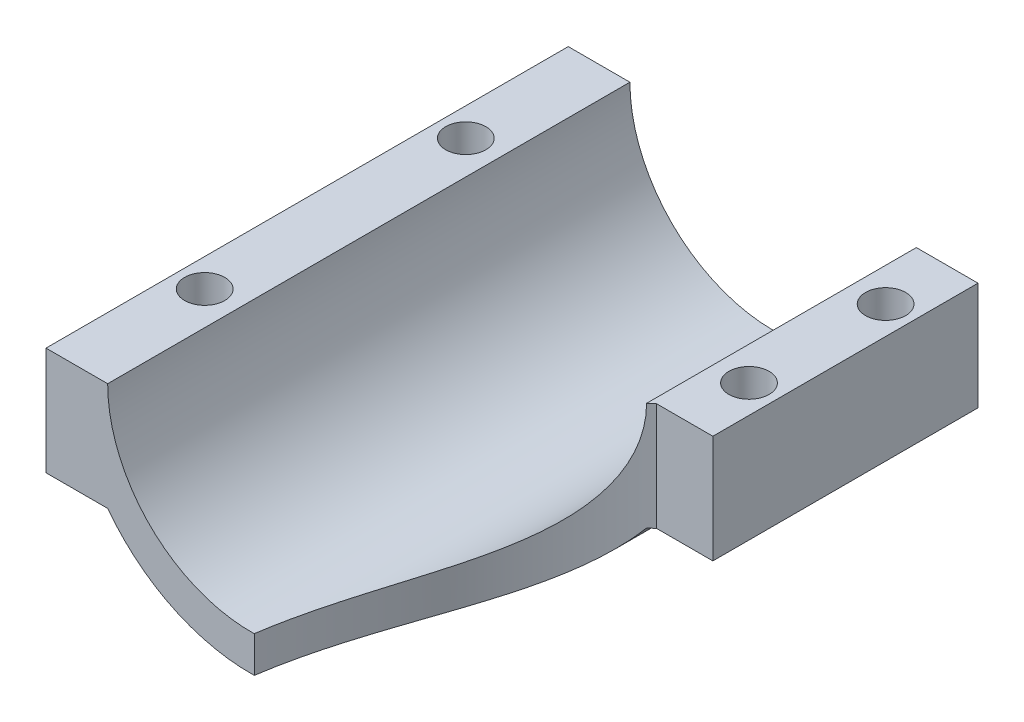
SolidWorks part; units mm, degrees
ref_plane "Front Plane" through (0, 0, 0) normal (0, 0, 1) x (1, 0, 0)
ref_plane "Top Plane" through (0, 0, 0) normal (0, 1, 0) x (1, 0, 0)
ref_plane "Right Plane" through (0, 0, 0) normal (1, 0, 0) x (0, 0, -1)
sketch "Sketch1" plane through (0, 0, 0) normal (0, 1, 0) x (1, 0, 0)
  line L4 (-18.5, -0.5) -> (-25.5, -0.5)
  line L5 (-25.5, -0.5) -> (-25.5, 32.5)
  line L6 (-22, -0.5) -> (-22, 32.5) construction
  line L7 (18.5, -32.5) -> (18.5, 32.5)
  line L8 (25.5, 32.5) -> (25.5, -32.5)
  line L9 (-18.5, -0.5) -> (-18.5, 32.5)
  line L10 (-25.5, 32.5) -> (25.5, 32.5)
  line L14 (25.5, -32.5) -> (-0.42, -32.5)
  line L22 (-18.5, 32.5) -> (18.5, -32.5) construction
  line L23 (-18.5, -0.5) -> (-18.5, -32.5) construction
  line L24 (-18.5, -32.5) -> (-0.42, -32.5) construction
  line L25 (-18.5, -32.5) -> (18.5, 32.5) construction
  arc A0 (-0.42, -32.5) -> (-18.5, -0.5) centre (-51.5792, -40.2973) ccw
  circle A1 centre (-22, 7.5) radius 2.5
  circle A2 centre (-22, 24.5) radius 2.5
  circle A3 centre (22, -16.25) radius 2.5
  circle A4 centre (22, 16.25) radius 2.5
  point P2 (0, 0)
  dimension "D3" = 5
  dimension "D4" = 5
  dimension "D9" = 5
  dimension "D10" = 5
  dimension "D11" = 3.5
  dimension "D12" = 8
  dimension "D13" = 32.5
  dimension "D14" = 16.25
  dimension "D17" = 51.75
  dimension "D1" = 7
  dimension "D2" = 33
  dimension "D5" = 17
  dimension "D6" = 51
  dimension "D7" = 3.5
  dimension "D8" = 3.5
  dimension "D15" = 16.25
  dimension "D16" = 18.08
extrude "Boss-Extrude1" add sketch "Sketch1" along normal blind 22.325 contours L14 L8 L10 L7 A4 A3 | A0 L14 L7 L10 L9 | L10 L5 L4 L9 A2 A1
sketch "Sketch2" plane through (0, 0, -32.5) normal (0, 0, -1) x (-1, 0, 0)
  line L0 (-21.8848, 22.325) -> (-17.825, 22.325) construction
  line L1 (-17.825, 22.325) -> (-17.825, -6.85) construction
  line L2 (24.5159, 22.325) -> (17.825, 22.325) construction
  line L3 (17.825, 22.325) -> (17.825, -6.85) construction
  line L4 (-17.825, 8.8835) -> (-25.5, 8.8835)
  line L5 (25.5, 8.8835) -> (17.825, 8.8835)
  line L6 (-25.5, 8.8835) -> (-25.5, -2.8834)
  line L7 (-25.5, -2.8834) -> (25.5, -2.8834)
  line L8 (25.5, -2.8834) -> (25.5, 8.8835)
  line L9 (-25.5, 22.325) -> (-25.5, 0) construction
  line L10 (25.5, 22.325) -> (25.5, 0) construction
  line L12 (25.5, 22.325) -> (-25.5, 22.325) construction
  line L13 (25.5, 0) -> (-25.5, 0) construction
  circle A0 centre (0, 22.325) radius 17.825
  arc A1 (-17.825, 8.8835) -> (17.825, 8.8835) centre (0, 22.325) ccw
  dimension "D1" = 35.65
  dimension "D2" = 11.7669
extrude "Cut-Extrude1" cut sketch "Sketch2" against normal through all
sketch "Sketch3" plane through (0, 8.8835, 0) normal (0, -1, 0) x (1, 0, 0)
  circle A0 centre (-22, -7.5) radius 6
  circle A1 centre (22, -16.25) radius 6
  circle A2 centre (22, 16.25) radius 6
  circle A3 centre (-22, -24.5) radius 6
  dimension "D1" = 12
  dimension "D2" = 12
  dimension "D3" = 12
  dimension "D4" = 12
extrude "Cut-Extrude2" cut sketch "Sketch3" along normal blind 22.325
mirror "Mirror2" about plane through (-25.5, 22.325, 0) normal (-1, 0, 0) of bodies 103
delete or keep bodies "Body-Delete/Keep 1" type delete bodies bodies 103
